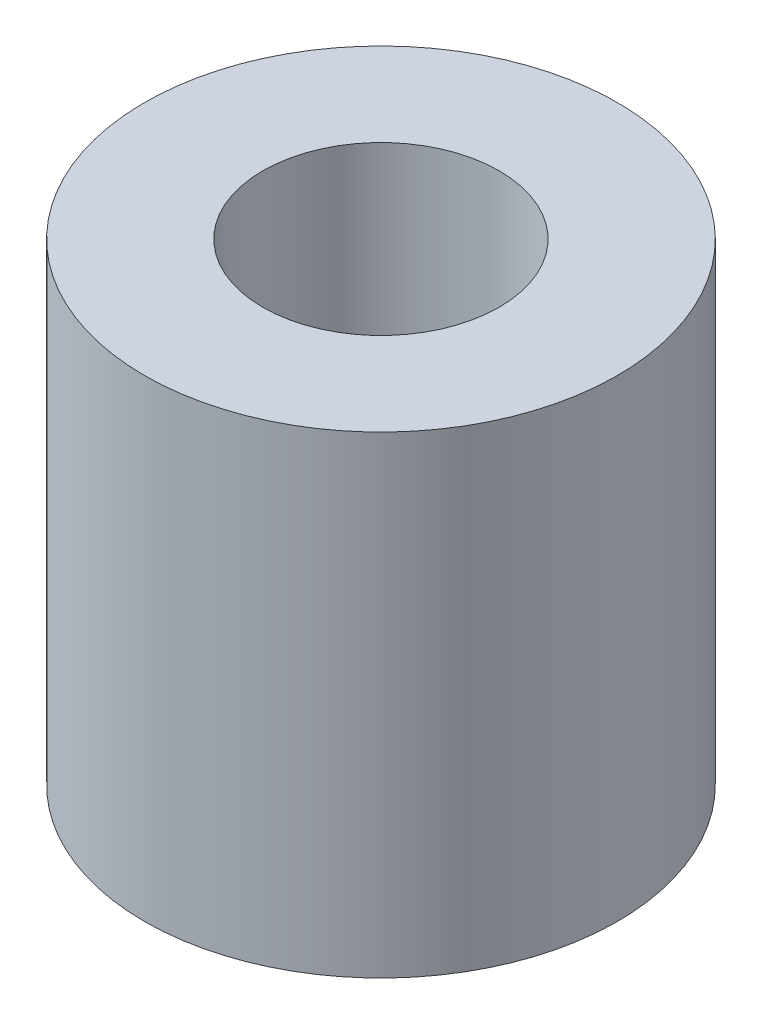
SolidWorks part; units mm, degrees
ref_plane "Front Plane" through (0, 0, 0) normal (0, 0, 1) x (1, 0, 0)
ref_plane "Top Plane" through (0, 0, 0) normal (0, 1, 0) x (1, 0, 0)
ref_plane "Right Plane" through (0, 0, 0) normal (1, 0, 0) x (0, 0, -1)
sketch "Sketch2" plane through (0, 0, 0) normal (0, 1, 0) x (1, 0, 0)
  circle A0 centre (0, 0) radius 40
  circle A1 centre (0, 0) radius 20
  dimension "D1" = 80
  dimension "D2" = 40
extrude "Boss-Extrude1" add sketch "Sketch2" against normal blind 80
